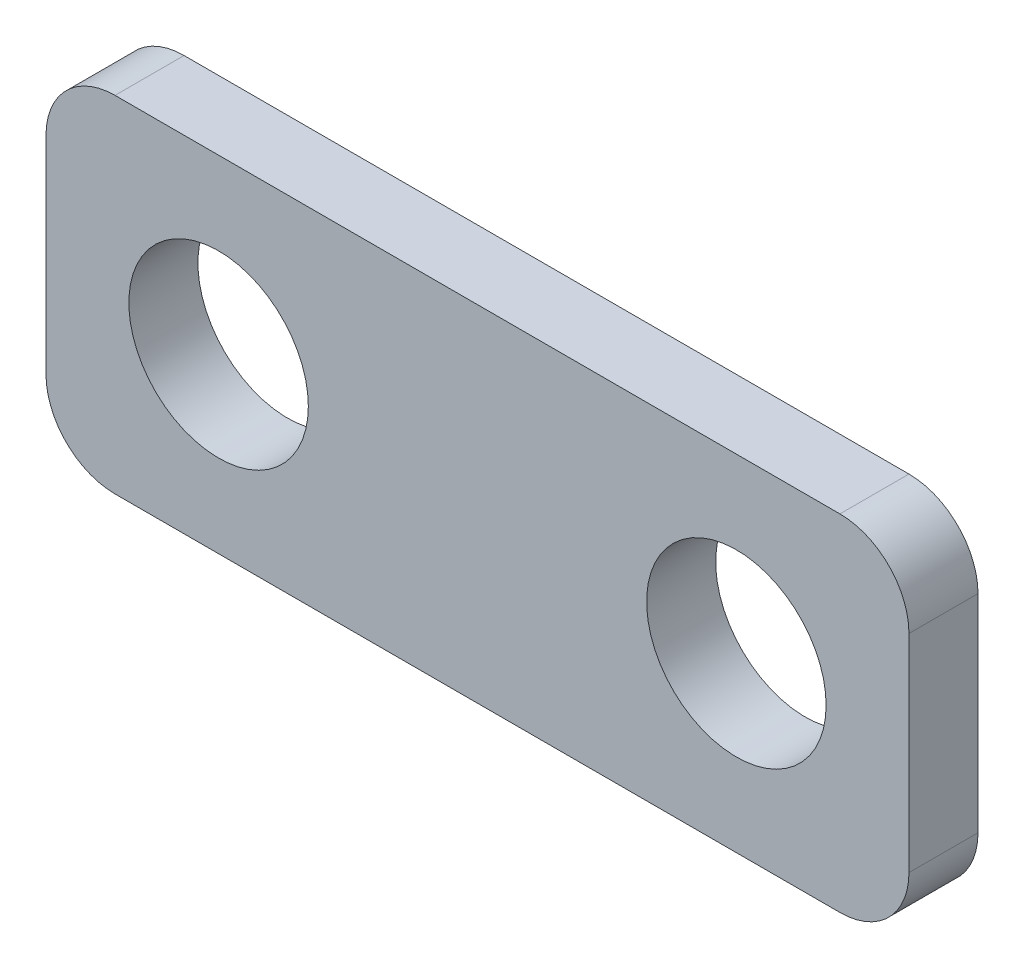
SolidWorks part; units mm, degrees
ref_plane "Front Plane" through (0, 0, 0) normal (0, 0, 1) x (1, 0, 0)
ref_plane "Top Plane" through (0, 0, 0) normal (0, 1, 0) x (1, 0, 0)
ref_plane "Right Plane" through (0, 0, 0) normal (1, 0, 0) x (0, 0, -1)
sketch "Sketch1" plane through (0, 0, 0) normal (0, 0, 1) x (1, 0, 0)
  line L0 (15.875, 12.7) -> (15.875, 0) construction
  line L1 (2.54, 0) -> (29.21, 0)
  line L2 (0, 2.54) -> (0, 10.16)
  line L3 (2.54, 12.7) -> (29.21, 12.7)
  line L4 (31.75, 2.54) -> (31.75, 10.16)
  circle A0 centre (6.35, 6.35) radius 3.302
  circle A1 centre (25.4, 6.35) radius 3.302
  arc A2 (29.21, 0) -> (31.75, 2.54) centre (29.21, 2.54) ccw
  arc A3 (2.54, 0) -> (0, 2.54) centre (2.54, 2.54) cw
  arc A4 (29.21, 12.7) -> (31.75, 10.16) centre (29.21, 10.16) cw
  arc A5 (0, 10.16) -> (2.54, 12.7) centre (2.54, 10.16) cw
  point P13 (31.75, 0)
  point P16 (0, 0)
  point P21 (0, 12.7)
  dimension "D3" = 6.604
  dimension "D6" = 2.54
  dimension "D1" = 31.75
  dimension "D2" = 12.7
  dimension "D4" = 9.525
  dimension "D5" = 6.35
extrude "Boss-Extrude1" add sketch "Sketch1" along normal blind 2.54
